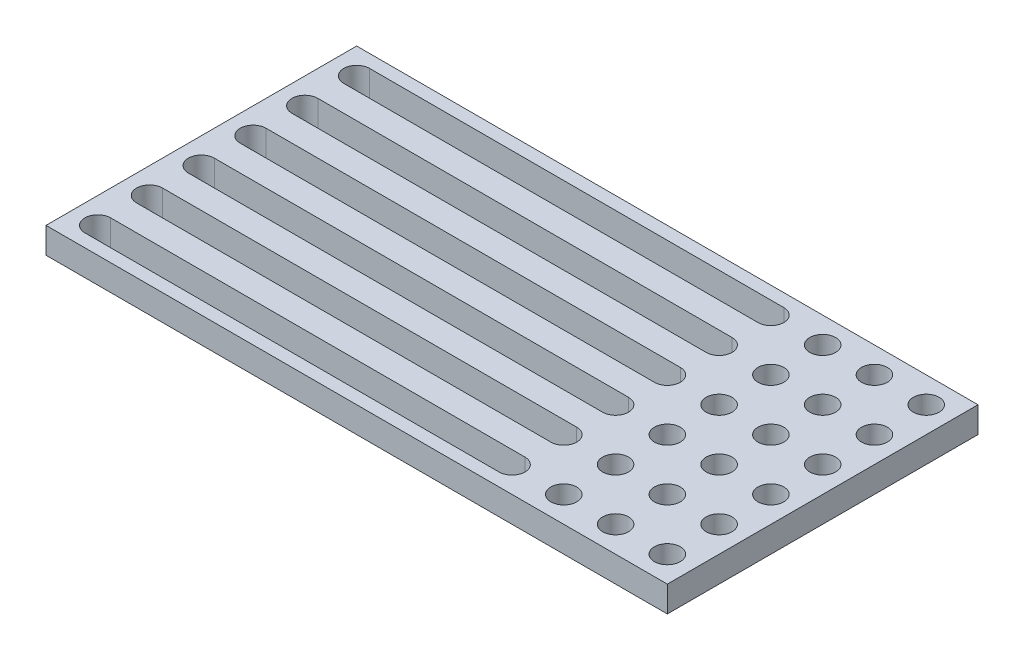
SolidWorks part; units mm, degrees
ref_plane "Front Plane" through (0, 0, 0) normal (0, 0, 1) x (1, 0, 0)
ref_plane "Top Plane" through (0, 0, 0) normal (0, 1, 0) x (1, 0, 0)
ref_plane "Right Plane" through (0, 0, 0) normal (1, 0, 0) x (0, 0, -1)
sketch "Sketch1" plane through (0, 0, 0) normal (0, 1, 0) x (1, 0, 0)
  line L0 (-76.2, 31.75) -> (76.2, 31.75) construction
  line L1 (-76.2, -38.1) -> (76.2, -38.1)
  line L2 (-76.2, -38.1) -> (-76.2, 38.1)
  line L3 (-76.2, 38.1) -> (76.2, 38.1)
  line L4 (76.2, -38.1) -> (76.2, 38.1)
  line L5 (-76.2, -38.1) -> (76.2, 38.1) construction
  line L6 (-76.2, 38.1) -> (76.2, -38.1) construction
  line L7 (-69.85, 34.925) -> (31.75, 34.925)
  line L8 (31.75, 15.875) -> (-69.85, 15.875)
  line L9 (31.75, 28.575) -> (-69.85, 28.575)
  line L10 (-69.85, 22.225) -> (31.75, 22.225)
  line L11 (31.75, 3.175) -> (-69.85, 3.175)
  line L12 (-69.85, 9.525) -> (31.75, 9.525)
  line L13 (31.75, -9.525) -> (-69.85, -9.525)
  line L14 (-69.85, -3.175) -> (31.75, -3.175)
  line L15 (31.75, -22.225) -> (-69.85, -22.225)
  line L16 (-69.85, -15.875) -> (31.75, -15.875)
  line L17 (31.75, -34.925) -> (-69.85, -34.925)
  line L18 (-69.85, -28.575) -> (31.75, -28.575)
  arc A0 (-69.85, 34.925) -> (-69.85, 28.575) centre (-69.85, 31.75) ccw
  arc A1 (31.75, 28.575) -> (31.75, 34.925) centre (31.75, 31.75) ccw
  circle A2 centre (44.45, 31.75) radius 3.175
  circle A3 centre (57.15, 31.75) radius 3.175
  circle A4 centre (69.85, 31.75) radius 3.175
  arc A5 (-69.85, 22.225) -> (-69.85, 15.875) centre (-69.85, 19.05) ccw
  arc A6 (31.75, 15.875) -> (31.75, 22.225) centre (31.75, 19.05) ccw
  circle A7 centre (44.45, 19.05) radius 3.175
  circle A8 centre (57.15, 19.05) radius 3.175
  circle A9 centre (69.85, 19.05) radius 3.175
  arc A10 (-69.85, 9.525) -> (-69.85, 3.175) centre (-69.85, 6.35) ccw
  arc A11 (31.75, 3.175) -> (31.75, 9.525) centre (31.75, 6.35) ccw
  circle A12 centre (44.45, 6.35) radius 3.175
  circle A13 centre (57.15, 6.35) radius 3.175
  circle A14 centre (69.85, 6.35) radius 3.175
  arc A15 (-69.85, -3.175) -> (-69.85, -9.525) centre (-69.85, -6.35) ccw
  arc A16 (31.75, -9.525) -> (31.75, -3.175) centre (31.75, -6.35) ccw
  circle A17 centre (44.45, -6.35) radius 3.175
  circle A18 centre (57.15, -6.35) radius 3.175
  circle A19 centre (69.85, -6.35) radius 3.175
  arc A20 (-69.85, -15.875) -> (-69.85, -22.225) centre (-69.85, -19.05) ccw
  arc A21 (31.75, -22.225) -> (31.75, -15.875) centre (31.75, -19.05) ccw
  circle A22 centre (44.45, -19.05) radius 3.175
  circle A23 centre (57.15, -19.05) radius 3.175
  circle A24 centre (69.85, -19.05) radius 3.175
  arc A25 (-69.85, -28.575) -> (-69.85, -34.925) centre (-69.85, -31.75) ccw
  arc A26 (31.75, -34.925) -> (31.75, -28.575) centre (31.75, -31.75) ccw
  circle A27 centre (44.45, -31.75) radius 3.175
  circle A28 centre (57.15, -31.75) radius 3.175
  circle A29 centre (69.85, -31.75) radius 3.175
  point P0 (0, 0)
  dimension "D4" = 6.35
  dimension "D7" = 6.35
  dimension "D1" = 76.2
  dimension "D2" = 152.4
  dimension "D3" = 6.35
  dimension "D5" = 6.35
  dimension "D6" = 101.6
  dimension "D8" = 12.7
  dimension "D9" = 3
  dimension "D10" = 6
extrude "Boss-Extrude1" add sketch "Sketch1" along normal blind 6.35
